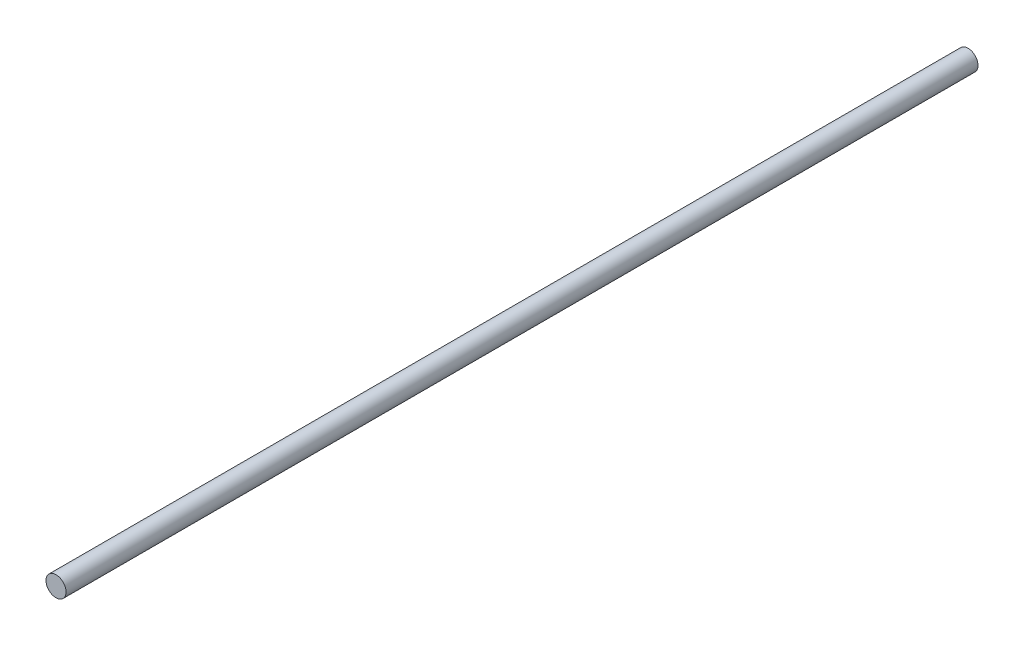
SolidWorks part; units mm, degrees
ref_plane "Plan de face" through (0, 0, 0) normal (0, 0, 1) x (1, 0, 0)
ref_plane "Plan de dessus" through (0, 0, 0) normal (0, 1, 0) x (1, 0, 0)
ref_plane "Plan de droite" through (0, 0, 0) normal (1, 0, 0) x (0, 0, -1)
sketch "Esquisse1" plane through (0, 0, 0) normal (0, 0, 1) x (1, 0, 0)
  circle A0 centre (0, 0) radius 3
extrude "Extrusion1" add sketch "Esquisse1" along normal blind 273
